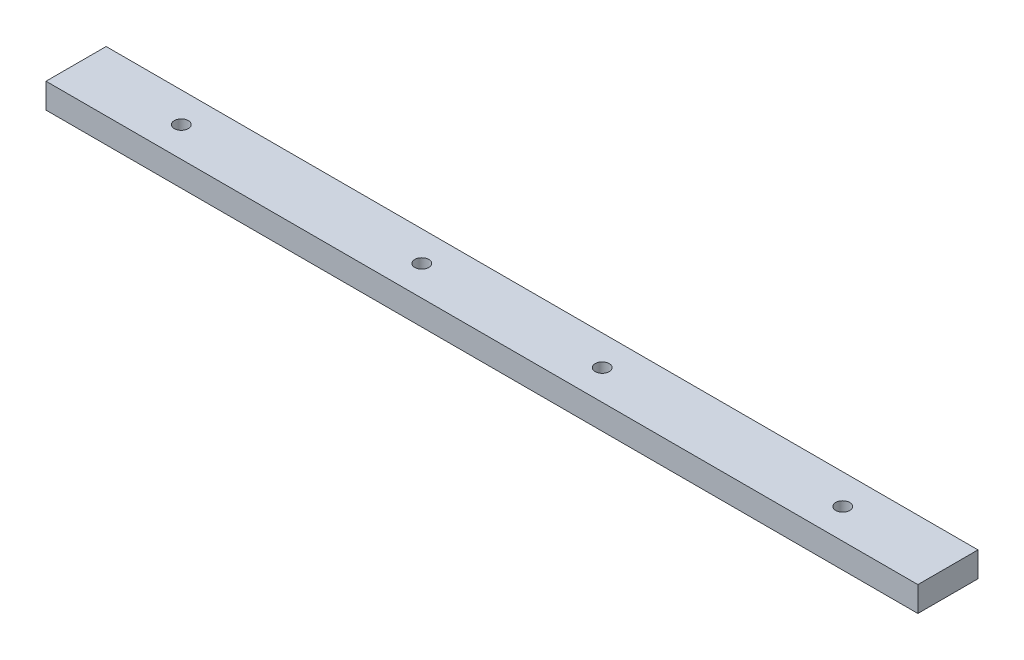
SolidWorks part; units mm, degrees
ref_plane "Front Plane" through (0, 0, 0) normal (0, 0, 1) x (1, 0, 0)
ref_plane "Top Plane" through (0, 0, 0) normal (0, 1, 0) x (1, 0, 0)
ref_plane "Right Plane" through (0, 0, 0) normal (1, 0, 0) x (0, 0, -1)
sketch "Sketch1" plane through (0, 0, 0) normal (0, 1, 0) x (1, 0, 0)
  line L0 (-18, 0) -> (18, 0) construction
  line L1 (-87, 6) -> (87, 6)
  line L2 (-87, 6) -> (-87, -6)
  line L3 (-87, -6) -> (87, -6)
  line L4 (87, 6) -> (87, -6)
  line L5 (-87, 6) -> (87, -6) construction
  line L6 (-87, -6) -> (87, 6) construction
  circle A0 centre (-66, 0) radius 1.4
  circle A1 centre (-18, 0) radius 1.4
  circle A2 centre (18, 0) radius 1.4
  circle A3 centre (66, 0) radius 1.4
  point P0 (0, 0)
  point P14 (0, 0)
  dimension "D3" = 2.8
  dimension "D1" = 174
  dimension "D2" = 12
  dimension "D4" = 48
  dimension "D5" = 36
  dimension "D6" = 48
extrude "Bottom screwhole block" add sketch "Sketch1" along normal blind 5
